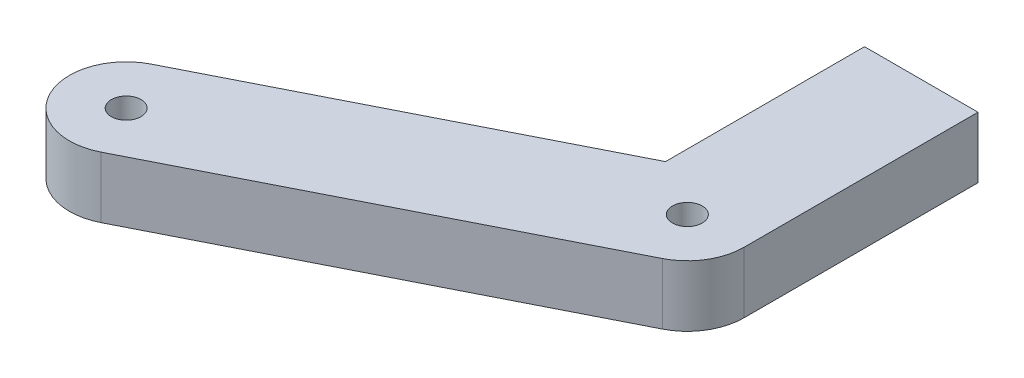
SolidWorks part; units mm, degrees
ref_plane "Front Plane" through (0, 0, 0) normal (0, 0, 1) x (1, 0, 0)
ref_plane "Top Plane" through (0, 0, 0) normal (0, 1, 0) x (1, 0, 0)
ref_plane "Right Plane" through (0, 0, 0) normal (1, 0, 0) x (0, 0, -1)
sketch "Sketch2" plane through (0, 0, 0) normal (0, 1, 0) x (1, 0, 0)
  line L0 (-14.7232, 30.7367) -> (27.9768, 52.3267) construction
  line L1 (-17.6562, 36.5374) -> (25.0438, 58.1274)
  line L2 (-11.7903, 24.936) -> (30.9097, 46.526)
  line L3 (27.9768, 52.3267) -> (27.9768, 72.3267) construction
  line L6 (21.4768, 52.3267) -> (21.4768, 72.3267)
  line L7 (34.4768, 52.3267) -> (34.4768, 72.3267)
  line L9 (21.4768, 72.3267) -> (34.4768, 72.3267)
  line L10 (21.4768, 72.3267) -> (21.4768, 79.1244)
  line L11 (21.4768, 79.1244) -> (34.4768, 79.1244)
  line L12 (34.4768, 72.3267) -> (34.4768, 79.1244)
  arc A0 (-17.6562, 36.5374) -> (-11.7903, 24.936) centre (-14.7232, 30.7367) ccw
  arc A1 (30.9097, 46.526) -> (25.0438, 58.1274) centre (27.9768, 52.3267) ccw
  circle A4 centre (27.9768, 52.3267) radius 1.7
  circle A5 centre (-14.7232, 30.7367) radius 1.7
  arc A6 (21.4768, 52.3267) -> (34.4768, 52.3267) centre (27.9768, 52.3267) ccw
  arc A7 (34.4768, 72.3267) -> (21.4768, 72.3267) centre (27.9768, 72.3267) ccw
  point P2 (6.6268, 41.5317)
  point P11 (27.9768, 62.3267)
  dimension "D1" = 3.4
  dimension "D2" = 3.4
extrude "Boss-Extrude1" add sketch "Sketch2" along normal blind 7
